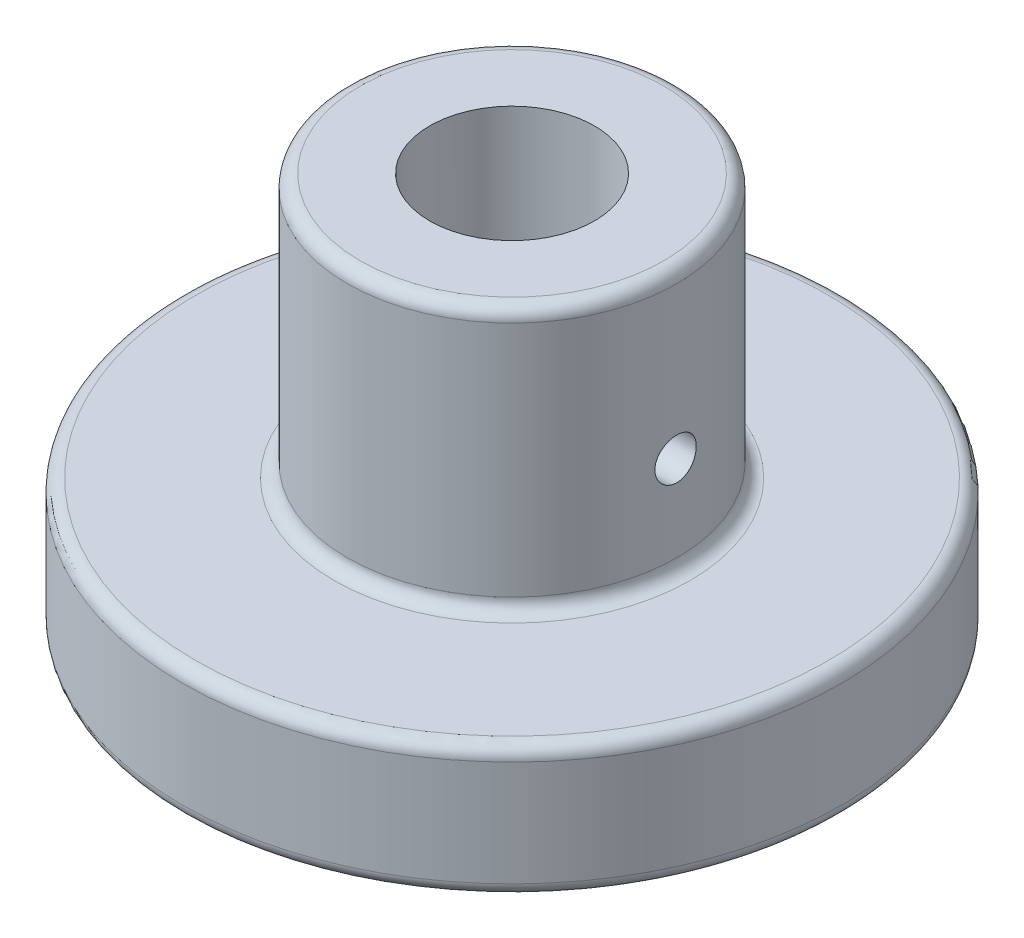
SolidWorks part; units mm, degrees
ref_plane "Front Plane" through (0, 0, 0) normal (0, 0, 1) x (1, 0, 0)
ref_plane "Top Plane" through (0, 0, 0) normal (0, 1, 0) x (1, 0, 0)
ref_plane "Right Plane" through (0, 0, 0) normal (1, 0, 0) x (0, 0, -1)
sketch "Sketch1" plane through (0, 0, 0) normal (0, 1, 0) x (1, 0, 0)
  circle A0 centre (0, 0) radius 50
  dimension "D1" = 100
extrude "Boss-Extrude1" add sketch "Sketch1" along normal blind 20
sketch "Sketch2" plane through (0, 20, 0) normal (0, 1, 0) x (1, 0, 0)
  circle A0 centre (0, 0) radius 25
  circle A1 centre (0, 0) radius 12.5
  dimension "D1" = 50
  dimension "D2" = 25
extrude "Boss-Extrude2" add sketch "Sketch2" along normal blind 40
fillet "Fillet1" radius 2 1 edges at (0, 0, 50)
fillet "Fillet2" radius 2 3 edges at (0, 20, 25) (0, 60, 25) (0, 20, 50)
sketch "Sketch3" plane through (0, 0, 0) normal (1, 0, 0) x (0, 0, -1)
  line L2 (12.5, 20) -> (-12.5, 20) construction
  circle A0 centre (0, 35) radius 3.1363
  dimension "D1" = 15
extrude "Cut-Extrude1" cut sketch "Sketch3" against normal mid plane 50
